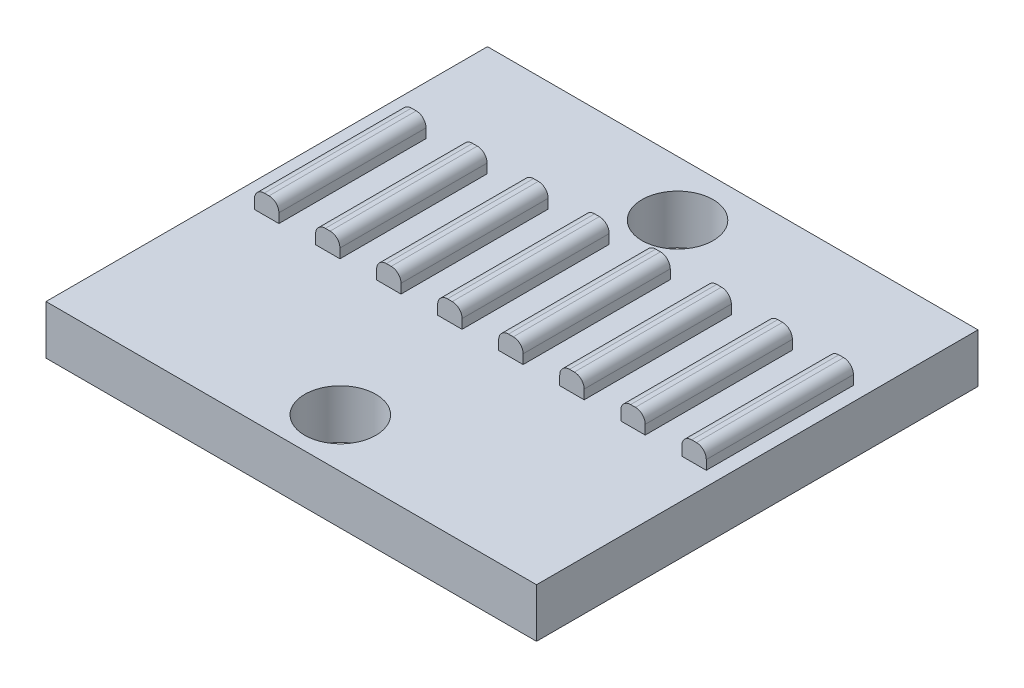
SolidWorks part; units mm, degrees
ref_plane "前视基准面" through (0, 0, 0) normal (0, 0, 1) x (1, 0, 0)
ref_plane "上视基准面" through (0, 0, 0) normal (0, 1, 0) x (1, 0, 0)
ref_plane "右视基准面" through (0, 0, 0) normal (1, 0, 0) x (0, 0, -1)
other "Configuration Table"
sketch "草图1" plane through (0, 0, 0) normal (0, 1, 0) x (1, 0, 0)
  line L1 (-10, 9) -> (10, 9)
  line L2 (-10, 9) -> (-10, -9)
  line L3 (-10, -9) -> (10, -9)
  line L4 (10, 9) -> (10, -9)
  line L5 (-10, 9) -> (10, -9) construction
  line L6 (-10, -9) -> (10, 9) construction
  point P0 (0, 0)
  dimension "D1" = 18
  dimension "D2" = 20
extrude "凸台-拉伸1" add sketch "草图1" along normal blind 2
extrude "切除-拉伸1" cut sketch "草图2" against normal blind 2
sketch "草图2" plane through (-240.6478, 2, 128.9977) normal (0, 1, 0) x (-0.0379, 0, 0.9993)
  circle A2 centre (-131.0286, 235.8523) radius 1.45
  circle A3 centre (-144.7687, 235.3313) radius 1.45
sketch "草图6" plane through (0, 2, 0) normal (0, 1, 0) x (1, 0, 0)
  line L0 (9.4213, 4.5) -> (8.4255, 4.5) construction
  line L1 (8.4255, 4.5) -> (8.4255, -1.5) construction
  line L2 (8.4255, -1.5) -> (9.4213, -1.5) construction
  line L3 (9.4213, -1.5) -> (9.4213, 4.5) construction
  line L4 (6.9319, 4.5) -> (5.9362, 4.5) construction
  line L5 (5.9362, 4.5) -> (5.9362, -1.5) construction
  line L6 (5.9362, -1.5) -> (6.9319, -1.5) construction
  line L7 (6.9319, -1.5) -> (6.9319, 4.5) construction
  line L8 (4.4426, 4.5) -> (3.4468, 4.5) construction
  line L9 (3.4468, 4.5) -> (3.4468, -1.5) construction
  line L10 (3.4468, -1.5) -> (4.4426, -1.5) construction
  line L11 (4.4426, -1.5) -> (4.4426, 4.5) construction
  line L12 (1.9532, 4.5) -> (0.9574, 4.5) construction
  line L13 (0.9574, 4.5) -> (0.9574, -1.5) construction
  line L14 (0.9574, -1.5) -> (1.9532, -1.5) construction
  line L15 (1.9532, -1.5) -> (1.9532, 4.5) construction
  line L16 (-0.5362, 4.5) -> (-1.5319, 4.5) construction
  line L17 (-1.5319, 4.5) -> (-1.5319, -1.5) construction
  line L18 (-1.5319, -1.5) -> (-0.5362, -1.5) construction
  line L19 (-0.5362, -1.5) -> (-0.5362, 4.5) construction
  line L20 (-3.0255, 4.5) -> (-4.0213, 4.5) construction
  line L21 (-4.0213, 4.5) -> (-4.0213, -1.5) construction
  line L22 (-4.0213, -1.5) -> (-3.0255, -1.5) construction
  line L23 (-3.0255, -1.5) -> (-3.0255, 4.5) construction
  line L24 (-5.5149, 4.5) -> (-6.5106, 4.5) construction
  line L25 (-6.5106, 4.5) -> (-6.5106, -1.5) construction
  line L26 (-6.5106, -1.5) -> (-5.5149, -1.5) construction
  line L27 (-5.5149, -1.5) -> (-5.5149, 4.5) construction
  line L28 (-9, 4.5) -> (-9, -1.5) construction
  line L29 (-9, -1.5) -> (-8.0043, -1.5) construction
  line L30 (-8.0043, -1.5) -> (-8.0043, 4.5) construction
  line L31 (-8.0043, 4.5) -> (-9, 4.5) construction
  line L32 (9.4213, 4.5) -> (8.4255, 4.5)
  line L33 (8.4255, 4.5) -> (8.4255, -1.5)
  line L34 (8.4255, -1.5) -> (9.4213, -1.5)
  line L35 (9.4213, -1.5) -> (9.4213, 4.5)
  line L36 (6.9319, 4.5) -> (5.9362, 4.5)
  line L37 (5.9362, 4.5) -> (5.9362, -1.5)
  line L38 (5.9362, -1.5) -> (6.9319, -1.5)
  line L39 (6.9319, -1.5) -> (6.9319, 4.5)
  line L40 (4.4426, 4.5) -> (3.4468, 4.5)
  line L41 (3.4468, 4.5) -> (3.4468, -1.5)
  line L42 (3.4468, -1.5) -> (4.4426, -1.5)
  line L43 (4.4426, -1.5) -> (4.4426, 4.5)
  line L44 (1.9532, 4.5) -> (0.9574, 4.5)
  line L45 (0.9574, 4.5) -> (0.9574, -1.5)
  line L46 (0.9574, -1.5) -> (1.9532, -1.5)
  line L47 (1.9532, -1.5) -> (1.9532, 4.5)
  line L48 (-0.5362, 4.5) -> (-1.5319, 4.5)
  line L49 (-1.5319, 4.5) -> (-1.5319, -1.5)
  line L50 (-1.5319, -1.5) -> (-0.5362, -1.5)
  line L51 (-0.5362, -1.5) -> (-0.5362, 4.5)
  line L52 (-3.0255, 4.5) -> (-4.0213, 4.5)
  line L53 (-4.0213, 4.5) -> (-4.0213, -1.5)
  line L54 (-4.0213, -1.5) -> (-3.0255, -1.5)
  line L55 (-3.0255, -1.5) -> (-3.0255, 4.5)
  line L56 (-5.5149, 4.5) -> (-6.5106, 4.5)
  line L57 (-6.5106, 4.5) -> (-6.5106, -1.5)
  line L58 (-6.5106, -1.5) -> (-5.5149, -1.5)
  line L59 (-5.5149, -1.5) -> (-5.5149, 4.5)
  line L60 (-9, 4.5) -> (-9, -1.5)
  line L61 (-9, -1.5) -> (-8.0043, -1.5)
  line L62 (-8.0043, -1.5) -> (-8.0043, 4.5)
  line L63 (-8.0043, 4.5) -> (-9, 4.5)
extrude "凸台-拉伸4" add sketch "草图6" along normal blind 0.78 separate body
fillet "圆角11" radius 0.4 2 edges at (-8.0043, 2.78, -1.5) (-9, 2.78, -1.5)
fillet "圆角12" radius 0.4 2 edges at (-5.5149, 2.78, -1.5) (-6.5106, 2.78, -1.5)
fillet "圆角13" radius 0.4 2 edges at (-3.0255, 2.78, -1.5) (-4.0213, 2.78, -1.5)
fillet "圆角14" radius 0.4 1 edges at (-1.5319, 2.78, -1.5)
fillet "圆角15" radius 0.4 1 edges at (-0.5362, 2.78, -1.5)
fillet "圆角16" radius 0.4 2 edges at (1.9532, 2.78, -1.5) (0.9574, 2.78, -1.5)
fillet "圆角17" radius 0.4 2 edges at (4.4426, 2.78, -1.5) (3.4468, 2.78, -1.5)
fillet "圆角18" radius 0.4 2 edges at (6.9319, 2.78, -1.5) (5.9362, 2.78, -1.5)
fillet "圆角19" radius 0.4 2 edges at (9.4213, 2.78, -1.5) (8.4255, 2.78, -1.5)
